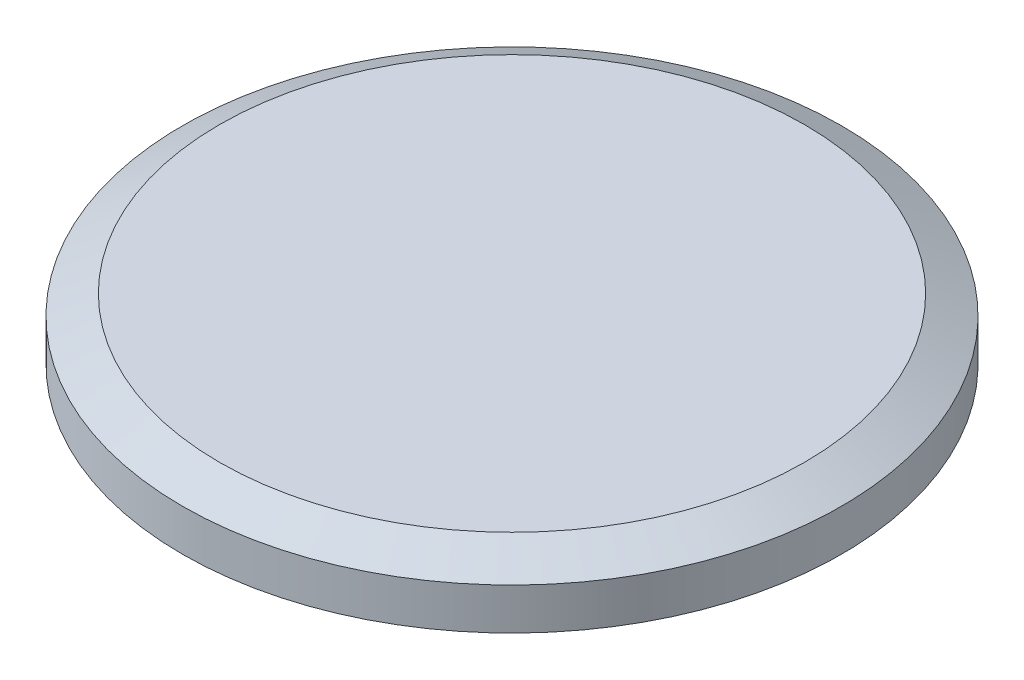
SolidWorks part; units mm, degrees
ref_plane "前基準面" through (0, 0, 0) normal (0, 0, 1) x (1, 0, 0)
ref_plane "上基準面" through (0, 0, 0) normal (0, 1, 0) x (1, 0, 0)
ref_plane "右基準面" through (0, 0, 0) normal (1, 0, 0) x (0, 0, -1)
sketch "Sketch1" plane through (0, 0, 0) normal (0, 0, 1) x (1, 0, 0)
  line L0 (0, 6.4475) -> (0, 12.6475)
  line L1 (0, 12.6475) -> (22.5, 12.6475)
  line L2 (22.5, 12.6475) -> (25.35, 11.1475)
  line L3 (25.35, 11.1475) -> (25.35, 7.9475)
  line L4 (25.35, 7.9475) -> (22.5, 6.4475)
  line L5 (22.5, 6.4475) -> (0, 6.4475)
  line L6 (0, 9.5475) -> (25.35, 9.5475) construction
  dimension "D1" = 6.2
  dimension "D2" = 3.2
  dimension "D3" = 22.5
  dimension "D4" = 25.35
revolve "Revolve1" add sketch "Sketch1" angle 360 about L0
